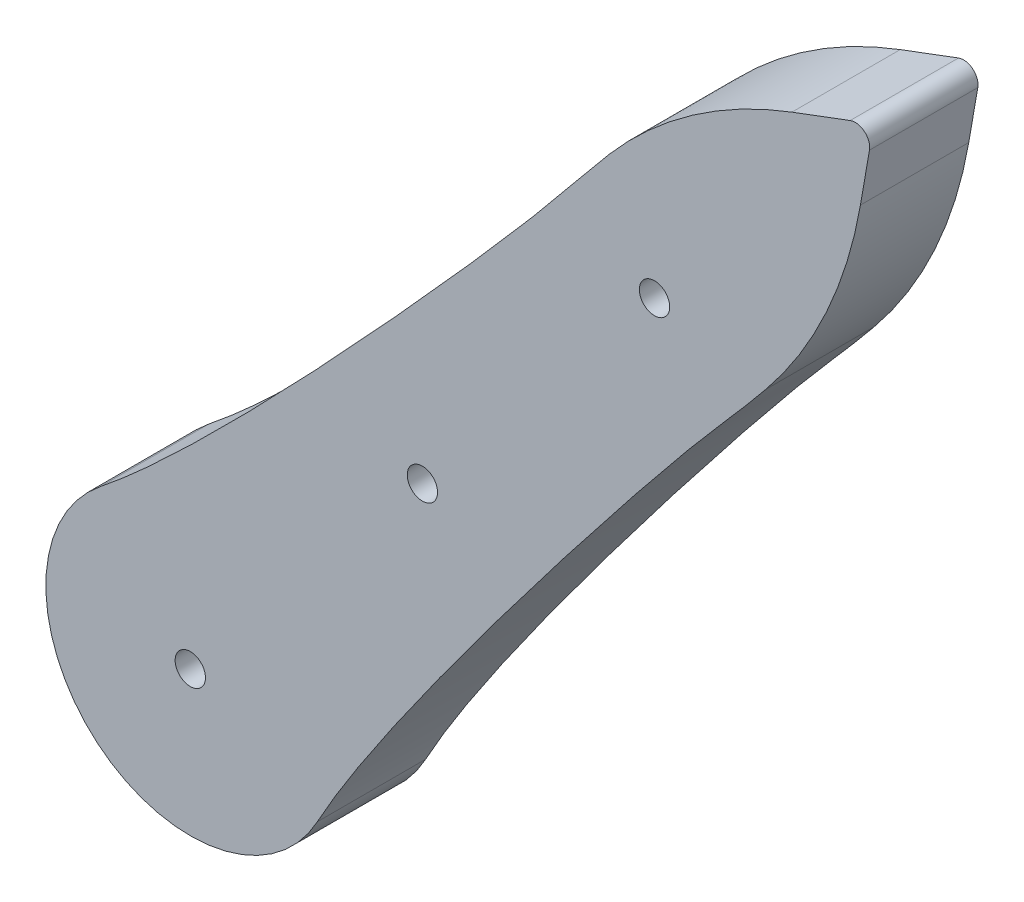
SolidWorks part; units mm, degrees
material "ABS"
ref_plane "Front Plane" through (0, 0, 0) normal (0, 0, 1) x (1, 0, 0)
ref_plane "Top Plane" through (0, 0, 0) normal (0, 1, 0) x (1, 0, 0)
ref_plane "Right Plane" through (0, 0, 0) normal (1, 0, 0) x (0, 0, -1)
sketch "Sketch3" plane through (0, 0, 16) normal (0, 0, 1) x (1, 0, 0)
  line L0 (141.7182, -118.9157) -> (13.1607, -272.1246) construction
  line L2 (135.2182, -125.4157) -> (148.2182, -125.4157) construction
  line L3 (135.2182, -125.4157) -> (135.2182, -112.4157) construction
  line L4 (135.2182, -112.4157) -> (148.2182, -112.4157) construction
  line L5 (148.2182, -125.4157) -> (148.2182, -112.4157) construction
  line L6 (135.2182, -125.4157) -> (148.2182, -112.4157) construction
  line L7 (135.2182, -112.4157) -> (148.2182, -125.4157) construction
  arc A0 (155.0191, -142.9851) -> (115.7048, -109.9965) centre (141.7182, -118.9157) ccw
  circle A1 centre (109.5788, -157.2179) radius 1.6 construction
  circle A2 centre (135.2182, -112.4157) radius 1.6
  arc A3 (0.7245, -256.4612) -> (30.7456, -281.652) centre (13.1607, -272.1246) ccw
  circle A4 centre (148.2182, -112.4157) radius 1.6
  circle A5 centre (148.2182, -125.4157) radius 1.6
  circle A6 centre (135.2182, -125.4157) radius 1.6
  circle A7 centre (77.4395, -195.5202) radius 1.6
  circle A8 centre (45.3001, -233.8224) radius 1.6
  circle A9 centre (13.1607, -272.1246) radius 1.6
  spline S0 degree 3 poles (115.7048, -109.9965) (101.9488, -150.1167) (78.1788, -171.7728) (58.7171, -197.0824) (16.357, -244.0495) (0.7245, -256.4612) knots 0 0 0 0 0.61909 0.71909 1 1 1 1
  spline S1 degree 3 poles (155.0191, -142.9851) (117.8971, -163.4989) (100.6976, -190.6684) (79.1521, -214.2294) (40.2542, -264.1017) (30.7456, -281.652) knots 0 0 0 0 0.61909 0.71909 1 1 1 1
extrude "Boss-Extrude1" add sketch "Sketch3" along normal blind 15
sketch "Sketch4" plane through (0, 0, 31) normal (0, 0, 1) x (1, 0, 0)
  line L1 (81.6816, -169.2386) -> (116.9009, -107.0687)
  line L5 (103.1733, -186.0751) -> (159.1617, -140.1754)
  line L6 (81.6816, -169.2386) -> (107.8011, -159.4411)
  line L7 (103.1733, -186.0751) -> (107.8011, -159.4411)
  arc A0 (159.1442, -140.1897) -> (116.9009, -107.0687) centre (141.7182, -118.9157) ccw
  arc A1 (159.1442, -140.1897) -> (116.9009, -107.0687) centre (141.7182, -118.9157) ccw
  spline S0 degree 3 poles (115.7048, -109.9965) (101.9488, -150.1167) (78.1788, -171.7728) (58.7171, -197.0824) (16.357, -244.0495) (0.7245, -256.4612) knots 0 0 0 0 0.61909 0.71909 1 1 1 1 construction
  spline S1 degree 3 poles (30.7456, -281.652) (40.2542, -264.1017) (79.1521, -214.2294) (100.6976, -190.6684) (117.8971, -163.4989) (155.0191, -142.9851) knots 0 0 0 0 0.28091 0.38091 1 1 1 1 construction
  dimension "D1" = 55
extrude "Cut-Extrude1" cut sketch "Sketch4" against normal blind 15
fillet "Fillet3" radius 62 2 edges at (81.6816, -169.2386, 23.5) (103.1733, -186.0751, 23.5)
sketch "Sketch5" plane through (0, 0, 31) normal (0, 0, 1) x (1, 0, 0)
  circle A1 centre (77.4395, -195.5202) radius 2.1
  circle A2 centre (45.3001, -233.8224) radius 2.1
  circle A3 centre (13.1607, -272.1246) radius 2.1
  dimension "D1" = 4.2
  dimension "D2" = 4.2
  dimension "D3" = 4.2
extrude "Cut-Extrude2" cut sketch "Sketch5" against normal blind 15
fillet "Fillet4" radius 2 1 edges at (107.8011, -159.4411, 23.5)
equation "\"thighLength\"=185"
equation "\"legLength\"=200"
equation "\"m3Thru\"=3.2"
equation "\"m4Thru\"=4.3"
equation "\"m3Insert\"=4.2"
equation "\"m4Insert\"=5.3"
equation "\"shoulder5mm\"=5.1"
equation "\"6706out\"=37.125"
equation "\"6706in\"=30"
equation "\"6904out\"=30.125"
equation "\"6904in\"=17"
equation "\"D1@Sketch5\"=\"m3Insert\" "
equation "\"D2@Sketch5\"=\"m3Insert\" "
equation "\"D3@Sketch5\"=\"m3Insert\" "
